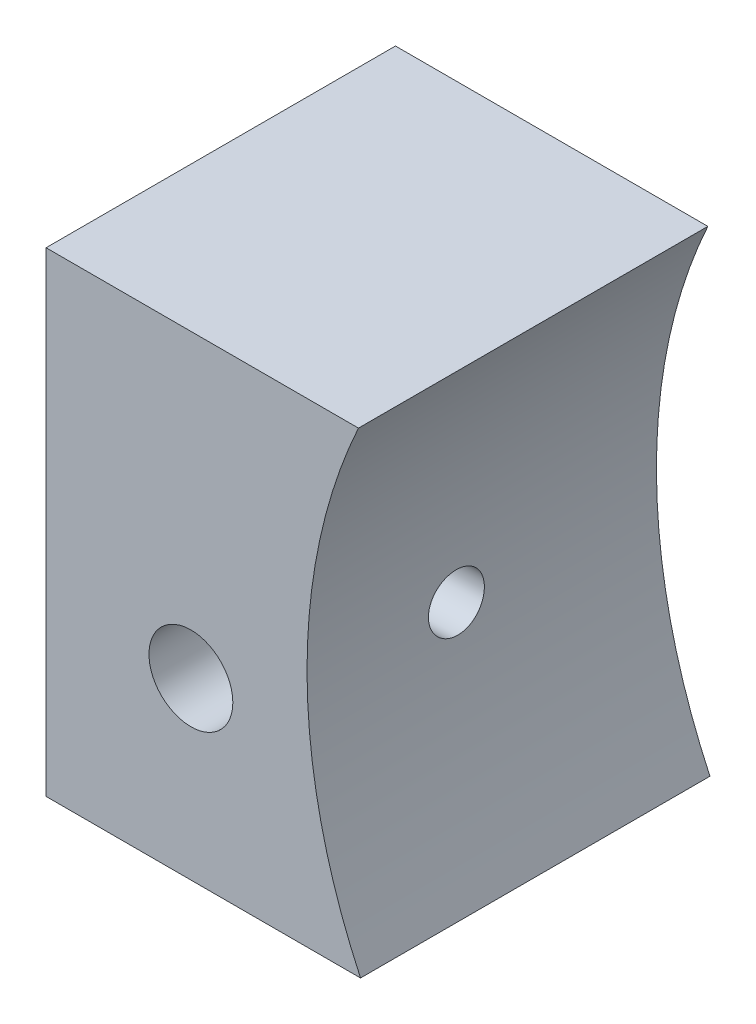
SolidWorks part; units mm, degrees
ref_plane "Plan de face" through (0, 0, 0) normal (0, 0, 1) x (1, 0, 0)
ref_plane "Plan de dessus" through (0, 0, 0) normal (0, 1, 0) x (1, 0, 0)
ref_plane "Plan de droite" through (0, 0, 0) normal (1, 0, 0) x (0, 0, -1)
sketch "Esquisse1" plane through (0, 0, 0) normal (0, 0, 1) x (1, 0, 0)
  line L0 (0, 0) -> (0, 68)
  line L1 (0, 68) -> (44.7041, 68)
  line L2 (0, 0) -> (45, 0)
  arc A0 (44.7041, 68) -> (45, 0) centre (118.0944, 34.3187) ccw
  dimension "D1" = 80.75
  dimension "D2" = 68
  dimension "D3" = 45
extrude "Boss.-Extru.1" add sketch "Esquisse1" along normal blind 50
shell "Coque2" thickness 10
hole_wizard "Trou taraudé #0-801" positions "Esquisse2" profile "Esquisse3" tap size "#0-80" standard "PCS" end condition through all
sketch "Esquisse2" plane through (0, 0, 50) normal (0, 0, 1) x (1, 0, 0)
  line L0 (0, 0) -> (45, 0) construction
  point P0 (20.7264, 25)
  dimension "D1" = 25
sketch "Esquisse3" plane through (20.7264, 25, 50) normal (1, 0, 0) x (0, -1, 0)
  line L0 (0, 0) -> (0, 50)
  line L1 (0, 50) -> (6, 50)
  line L2 (6, 50) -> (6, 0)
  line L5 (6, 0) -> (0, 0)
  line L11 (0, -6.35) -> (0, 107.95) construction
  dimension "Diamètre du trou pour taraudage jusqu'au prochain" = 12
  dimension "Profondeur du trou pour taraudage jusqu'au prochain" = 50
cosmetic thread "Filetage de perçage1"
hole_wizard "Trou de passage d'axe 3/321" positions "Esquisse3D1" profile "Esquisse4" hole size "3/32" standard "PCS"
sketch3d "Esquisse3D1"
  point P0 (37.3746, 32.1088, 28.6579)
sketch "Esquisse4" plane through (37.3746, 32.1088, 28.6579) normal (0, 0, 1) x (-0.0274, 0.9996, 0)
  line L0 (0, 0) -> (0, 10)
  line L1 (0, 10) -> (4, 10)
  line L2 (4, 10) -> (4, 0)
  line L5 (4, 0) -> (0, 0)
  line L11 (0, -6.35) -> (0, 107.95) construction
  arc A0 (35.6772, -8.309) -> (-32.3054, -6.7438) centre (0, -80.75) ccw construction
  dimension "Diamètre du perçage jusqu'au prochain" = 8
  dimension "Profondeur du perçage jusqu'au prochain" = 10
